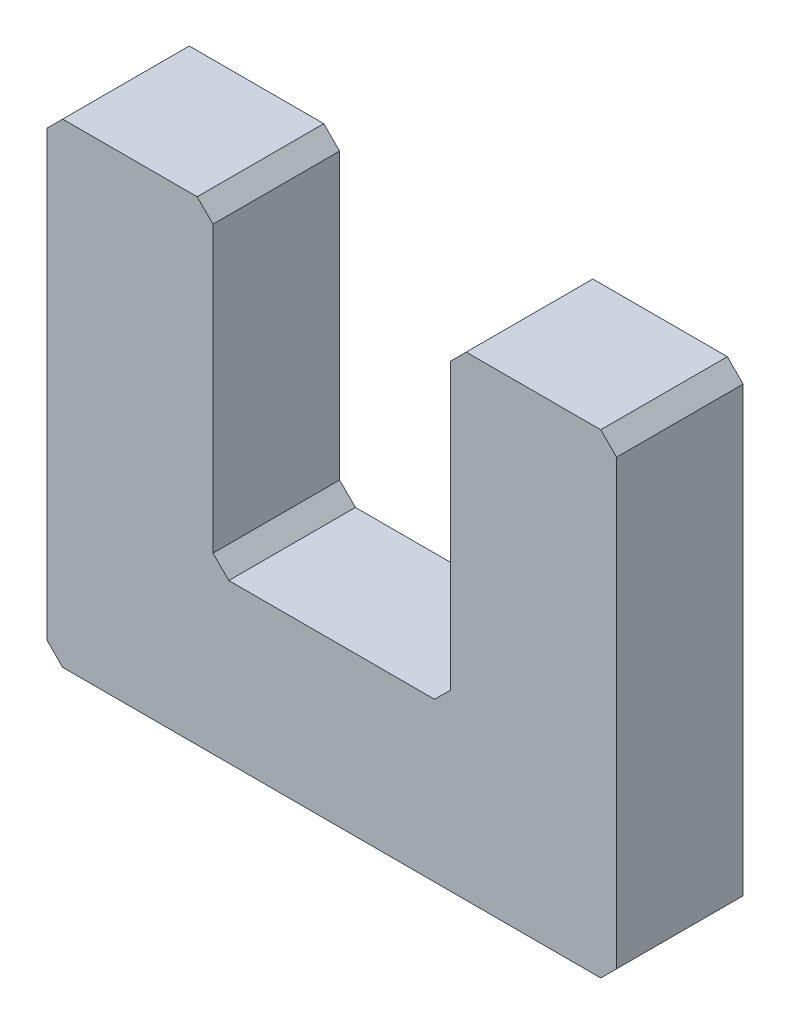
SolidWorks part; units mm, degrees
ref_plane "前视基准面" through (0, 0, 0) normal (0, 0, 1) x (1, 0, 0)
ref_plane "上视基准面" through (0, 0, 0) normal (0, 1, 0) x (1, 0, 0)
ref_plane "右视基准面" through (0, 0, 0) normal (1, 0, 0) x (0, 0, -1)
sketch "草图1" plane through (0, 0, 0) normal (0, 0, 1) x (1, 0, 0)
  line L1 (-18, -15) -> (18, -15)
  line L2 (-18, -15) -> (-18, 15)
  line L3 (-18, 15) -> (18, 15)
  line L4 (18, -15) -> (18, 15)
  line L5 (-18, -15) -> (18, 15) construction
  line L6 (-18, 15) -> (18, -15) construction
  point P0 (0, 0)
  dimension "D1" = 30
  dimension "D2" = 36
extrude "凸台-拉伸1" add sketch "草图1" along normal blind 8
sketch "草图9" plane through (0, 0, 8) normal (0, 0, 1) x (1, 0, 0)
  line L0 (0, 15) -> (0, 5) construction
  line L1 (18, 15) -> (-18, 15) construction
  line L2 (7.5, 15) -> (7.5, -5)
  line L3 (-7.5, 15) -> (-7.5, -5)
  line L4 (7.5, -5) -> (-7.5, -5)
  line L5 (-7.5, 15) -> (7.5, 15)
  point P4 (0, 10)
  dimension "D1" = 15
  dimension "D2" = 20
extrude "切除-拉伸1" cut sketch "草图9" against normal up to next
chamfer "倒角1" distance 1 angle 45 4 edges at (-18, -15, 4) (-18, 15, 4) (18, -15, 4) (18, 15, 4)
chamfer "倒角2" distance 1 angle 45 2 edges at (7.5, 15, 4) (-7.5, 15, 4)
chamfer "倒角3" distance 1 angle 45 2 edges at (7.5, -5, 4) (-7.5, -5, 4)
